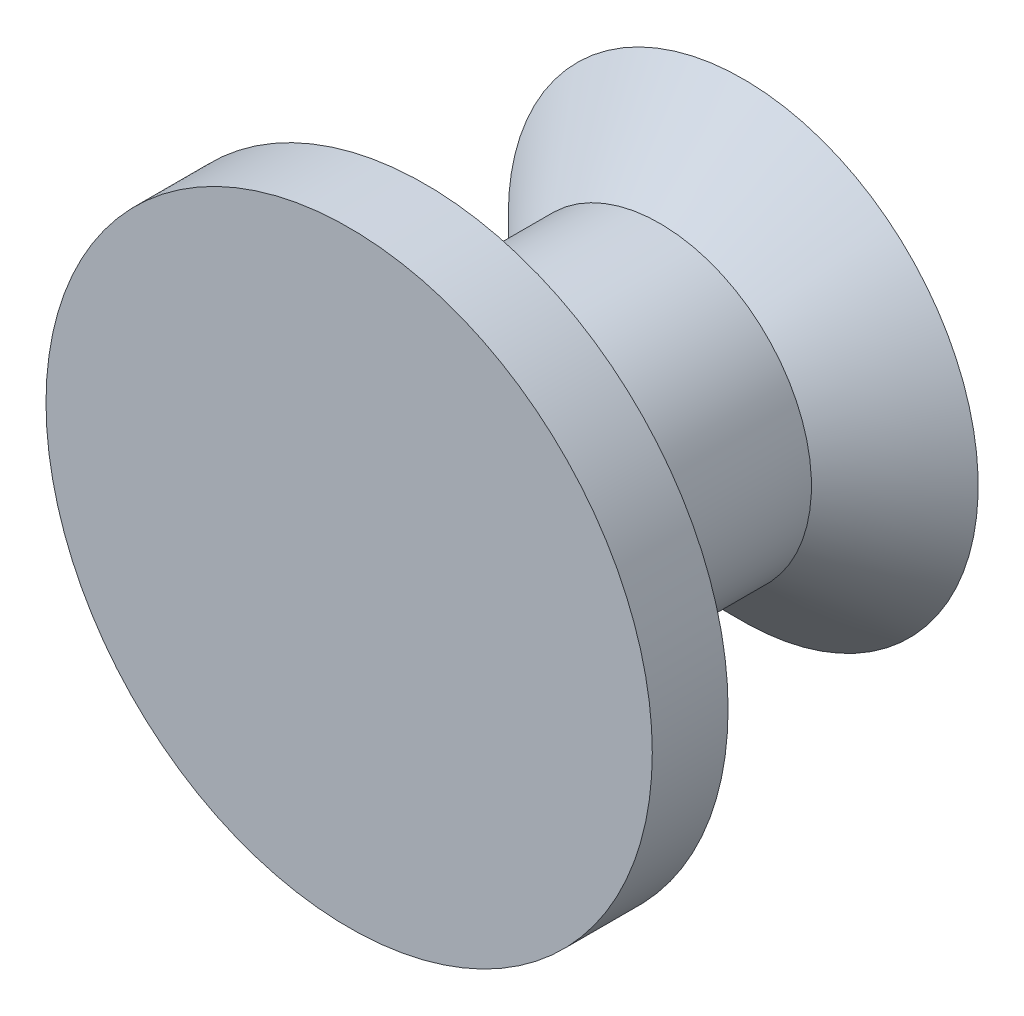
SolidWorks part; units mm, degrees
ref_plane "Front Plane" through (0, 0, 0) normal (0, 0, 1) x (1, 0, 0)
ref_plane "Top Plane" through (0, 0, 0) normal (0, 1, 0) x (1, 0, 0)
ref_plane "Right Plane" through (0, 0, 0) normal (1, 0, 0) x (0, 0, -1)
sketch "Sketch2" plane through (0, 0, 0) normal (0, 1, 0) x (1, 0, 0)
  line L0 (0, 0) -> (-2, 0)
  line L1 (-2, 0) -> (-2, 0.5)
  line L2 (-2, 0.5) -> (-1, 0.5)
  line L3 (-1, 0.5) -> (-1, 2.05)
  line L4 (-1, 2.05) -> (-1.55, 2.6)
  line L5 (-1.55, 2.6) -> (0, 2.6)
  line L6 (0, 2.6) -> (0, 0)
  dimension "D1" = 2
  dimension "D2" = 2.6
  dimension "D3" = 0.5
  dimension "D4" = 1
  dimension "D5" = 1.55
  dimension "D6" = 45
revolve "Revolve1" add sketch "Sketch2" angle 360 about L6
